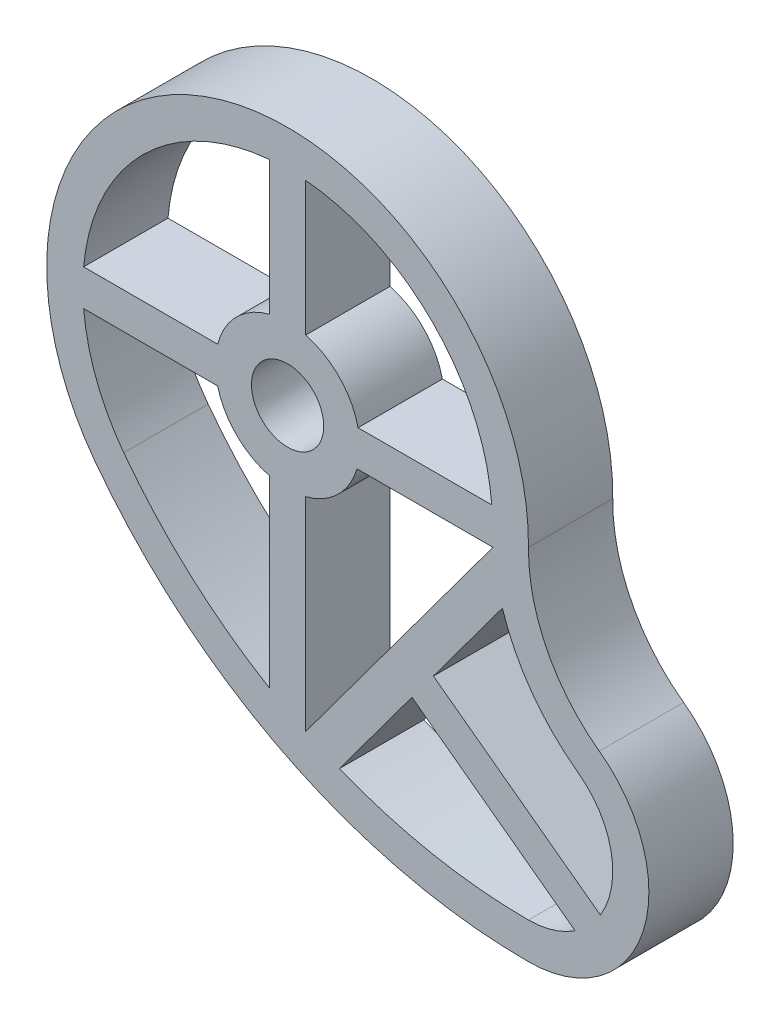
SolidWorks part; units mm, degrees
ref_plane "Front Plane" through (0, 0, 0) normal (0, 0, 1) x (1, 0, 0)
ref_plane "Top Plane" through (0, 0, 0) normal (0, 1, 0) x (1, 0, 0)
ref_plane "Right Plane" through (0, 0, 0) normal (1, 0, 0) x (0, 0, -1)
sketch "Sketch1" plane through (0, 0, 0) normal (0, 0, 1) x (1, 0, 0)
  arc A0 (19.9989, -0.2058) -> (-16, -12) centre (0, 0) ccw
  arc A1 (20, -30) -> (25.8836, -11.914) centre (20, -20) ccw
  arc A2 (19.9989, -0.2058) -> (25.8836, -11.914) centre (34.2959, -0.3529) ccw
  arc A3 (-16, -12) -> (20, -30) centre (20, 15) ccw
  circle A4 centre (0, 0) radius 3
  dimension "D1" = 40
  dimension "D2" = 20
  dimension "D5" = 6
  dimension "D6" = 58.2843
  dimension "D3" = 20
  dimension "D4" = 20
extrude "Boss-Extrude2" add sketch "Sketch1" along normal blind 7 contours A0 A3 A1 A2 A4
sketch "Sketch2" plane through (0, 0, 7) normal (0, 0, 1) x (1, 0, 0)
  line L12 (-11.8754, 12.1645) -> (-4.1913, 4.2933)
  line L13 (16.5034, 11.2977) -> (0, 0) construction
  line L14 (0, 17) -> (0, 6)
  line L16 (1.0682, 5.9041) -> (2.0283, 16.8786)
  line L20 (13.2611, 10.6369) -> (4.8487, 3.5342)
  line L23 (16.9991, -0.1749) -> (6, 0)
  line L24 (-17, 0) -> (-6, 0)
  line L25 (-13.6, -10.2) -> (-4.5983, -3.8543)
  line L26 (-13.0228, 10.9274) -> (-4.6802, 3.7545)
  line L27 (14.2459, 9.2765) -> (5.2373, 2.9276)
  line L28 (-16.675, -3.3084) -> (-5.8853, -1.1677)
  circle A20 centre (0, 0) radius 6
  circle A21 centre (0, 0) radius 6
  arc A22 (16.9991, -0.1749) -> (24.1186, -14.3398) centre (34.2959, -0.3529) ccw
  arc A23 (20, -27) -> (24.1186, -14.3398) centre (20, -20) ccw
  arc A24 (-13.6, -10.2) -> (20, -27) centre (20, 15) ccw
  arc A25 (16.9991, -0.1749) -> (-13.6, -10.2) centre (0, 0) ccw
  arc A26 (16.9991, -0.1749) -> (24.1186, -14.3398) centre (34.2959, -0.3529) ccw
  arc A27 (20, -27) -> (24.1186, -14.3398) centre (20, -20) ccw
  arc A28 (-13.6, -10.2) -> (20, -27) centre (20, 15) ccw
  arc A29 (16.9991, -0.1749) -> (-13.6, -10.2) centre (0, 0) ccw
  dimension "D2" = 3
  dimension "D3" = 3
  dimension "D4" = 7.6841
  dimension "D5" = 5
  dimension "D6" = 175
  dimension "D7" = 41.086
  dimension "D8" = 175
  dimension "D13" = 20
extrude "Cut-Extrude1" [suppressed] cut sketch "Sketch2" against normal blind 10
sketch "Sketch4" plane through (0, 0, 0) normal (0, 0, 1) x (1, 0, 0)
  line L0 (5.7615, -1.6749) -> (17.0488, -1.6749)
  line L1 (1.5, 16.9337) -> (1.5, 5.8095)
  line L2 (-1.5, 16.9337) -> (-1.5, 5.8095)
  line L3 (-6, 0) -> (-17, 0)
  line L4 (5.8519, 1.3251) -> (16.9483, 1.3251)
  line L5 (-5.8095, 1.5) -> (-16.9337, 1.5)
  line L6 (-5.8095, -1.5) -> (-16.9337, -1.5)
  line L7 (-1.5, -5.8095) -> (-1.5, -21.0798)
  line L8 (1.5, -5.8095) -> (1.5, -22.7061)
  line L9 (1.5, -22.7061) -> (17.0488, -1.6749)
  line L10 (4.3057, -23.9575) -> (17.8327, -5.6609)
  line L11 (10.3231, -15.8184) -> (23.8693, -25.8334)
  line L12 (12.1066, -13.4061) -> (25.9697, -23.6554)
  circle A12 centre (0, 0) radius 6
  circle A13 centre (0, 0) radius 6
  arc A14 (-13.6, -10.2) -> (20, -27) centre (20, 15) ccw
  arc A15 (20, -27) -> (24.1186, -14.3398) centre (20, -20) ccw
  arc A16 (16.9991, -0.1749) -> (24.1186, -14.3398) centre (34.2959, -0.3529) ccw
  arc A17 (16.9991, -0.1749) -> (-13.6, -10.2) centre (0, 0) ccw
  arc A18 (-13.6, -10.2) -> (20, -27) centre (20, 15) ccw
  arc A19 (20, -27) -> (24.1186, -14.3398) centre (20, -20) ccw
  arc A20 (16.9991, -0.1749) -> (24.1186, -14.3398) centre (34.2959, -0.3529) ccw
  arc A21 (16.9991, -0.1749) -> (-13.6, -10.2) centre (0, 0) ccw
  dimension "D6" = 1.5
  dimension "D3" = 1.5
  dimension "D4" = 1.5
  dimension "D5" = 3
  dimension "D7" = 1.5
  dimension "D8" = 1.5
  dimension "D9" = 3
  dimension "D10" = 3
  dimension "D11" = 16.8464
  dimension "D1" = 3
  dimension "D2" = 3
extrude "Cut-Extrude2" cut sketch "Sketch4" along normal blind 10 contours L6 A21 A18 L7 A13 | L2 A21 L5 A13 | L4 A21 L1 A13 | A13 L8 L9 L0 | A20 L10 L12 A19 | A18 A19 L11 L10
